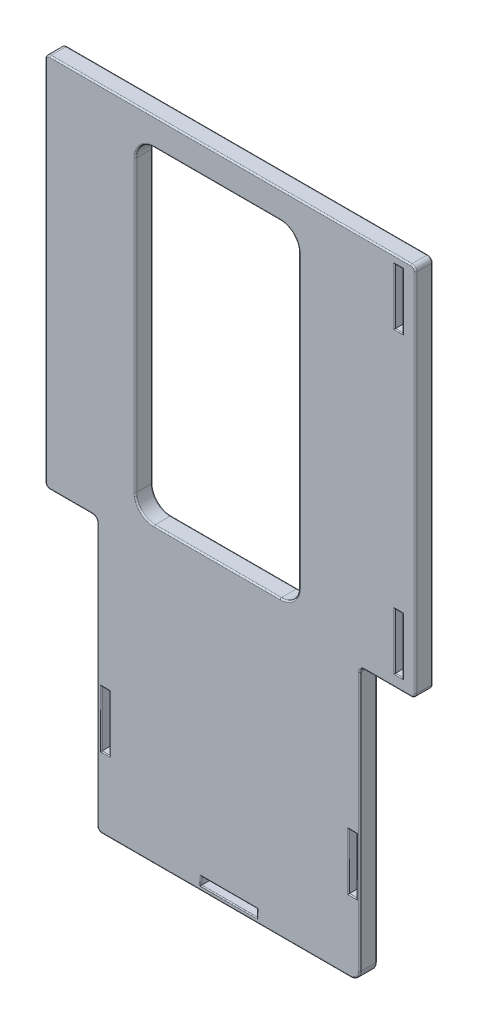
SolidWorks part; units mm, degrees
ref_plane "Front Plane" through (0, 0, 0) normal (0, 0, 1) x (1, 0, 0)
ref_plane "Top Plane" through (0, 0, 0) normal (0, 1, 0) x (1, 0, 0)
ref_plane "Right Plane" through (0, 0, 0) normal (1, 0, 0) x (0, 0, -1)
sketch "Sketch1" plane through (0, 0, 0) normal (0, 0, 1) x (1, 0, 0)
  line L0 (25.4709, 239.3333) -> (35.393, 239.3333)
  line L1 (-19.5605, 313.6323) -> (7.4395, 313.6323)
  line L2 (-23.5605, 309.6323) -> (-23.5605, 247.6323)
  line L3 (-19.5605, 243.6323) -> (7.4395, 243.6323)
  line L4 (11.4395, 309.6323) -> (11.4395, 247.6323)
  line L5 (36.393, 240.3333) -> (36.393, 318.4891)
  line L6 (35.393, 319.4891) -> (-41.857, 319.4891)
  line L7 (-42.857, 318.4891) -> (-42.857, 240.0833)
  line L9 (-41.857, 239.0833) -> (-32.7586, 239.0833)
  line L10 (-31.7586, 238.0833) -> (-31.7586, 181.8891)
  line L16 (-33.0086, 238.8333) -> (-42.107, 238.8333) construction
  line L17 (-32.0086, 209.8891) -> (-32.0086, 237.8333) construction
  line L20 (-32.0086, 181.3891) -> (-32.0086, 209.8891) construction
  line L21 (23.9709, 180.3891) -> (-31.0086, 180.3891) construction
  line L22 (24.9709, 209.8891) -> (24.9709, 181.3891) construction
  line L25 (24.9709, 237.8333) -> (24.9709, 209.8891) construction
  line L44 (34.893, 238.8333) -> (25.9709, 238.8333) construction
  line L61 (36.893, 318.8412) -> (36.893, 240.8333) construction
  line L73 (24.4709, 238.3333) -> (24.4709, 182.8891)
  line L74 (22.4709, 180.8891) -> (-30.7586, 180.8891)
  line L96 (24.9709, 182.3891) -> (24.9709, 217.4411) construction
  line L97 (-22.9709, 180.3891) -> (22.9709, 180.3891) construction
  line L100 (-41.9592, 319.9891) -> (35.7452, 319.9891) construction
  line L101 (-43.107, 239.8333) -> (-43.107, 318.8412) construction
  arc A0 (-23.5605, 247.6323) -> (-19.5605, 243.6323) centre (-19.5605, 247.6323) ccw
  arc A1 (-19.5605, 313.6323) -> (-23.5605, 309.6323) centre (-19.5605, 309.6323) ccw
  arc A5 (7.4395, 313.6323) -> (11.4395, 309.6323) centre (7.4395, 309.6323) cw
  arc A25 (7.4395, 243.6323) -> (11.4395, 247.6323) centre (7.4395, 247.6323) ccw
  arc A29 (-42.857, 240.0833) -> (-41.857, 239.0833) centre (-41.857, 240.0833) ccw
  arc A65 (-32.7586, 239.0833) -> (-31.7586, 238.0833) centre (-32.7586, 238.0833) cw
  arc A66 (-31.7586, 181.8891) -> (-30.7586, 180.8891) centre (-30.7586, 181.8891) ccw
  arc A67 (25.4709, 239.3333) -> (24.4709, 238.3333) centre (25.4709, 238.3333) ccw
  arc A68 (35.393, 239.3333) -> (36.393, 240.3333) centre (35.393, 240.3333) ccw
  arc A69 (36.393, 318.4891) -> (35.393, 319.4891) centre (35.393, 318.4891) ccw
  arc A70 (-41.857, 319.4891) -> (-42.857, 318.4891) centre (-41.857, 318.4891) ccw
  arc A72 (-43.107, 239.8333) -> (-42.107, 238.8333) centre (-42.107, 239.8333) ccw construction
  arc A73 (-32.0086, 237.8333) -> (-33.0086, 238.8333) centre (-33.0086, 237.8333) ccw construction
  arc A74 (-32.0086, 181.3891) -> (-31.0086, 180.3891) centre (-31.0086, 181.3891) ccw construction
  arc A75 (23.9709, 180.3891) -> (24.9709, 181.3891) centre (23.9709, 181.3891) ccw construction
  arc A76 (25.9709, 238.8333) -> (24.9709, 237.8333) centre (25.9709, 237.8333) ccw construction
  arc A77 (34.893, 238.8333) -> (36.893, 240.8333) centre (34.893, 240.8333) ccw construction
  arc A78 (36.893, 318.8412) -> (35.7452, 319.9891) centre (35.7452, 318.8412) ccw construction
  arc A79 (-41.9592, 319.9891) -> (-43.107, 318.8412) centre (-41.9592, 318.8412) ccw construction
  arc A95 (24.4709, 182.8891) -> (22.4709, 180.8891) centre (22.4709, 182.8891) cw
  dimension "D9" = 2
  dimension "D10" = 0.5
  dimension "D11" = 4
  dimension "D14" = 1
  dimension "D2" = 0.5
  dimension "D3" = 0.5
  dimension "D4" = 0.5
  dimension "D5" = 0.5
  dimension "D6" = 0.5
  dimension "D7" = 0.5
  dimension "D8" = 0.5
  dimension "D12" = 35
  dimension "D13" = 70
extrude "Boss-Extrude1" add sketch "Sketch1" along normal blind 3.7
sketch "Sketch2" plane through (0, 0, 0) normal (0, 0, -1) x (-1, 0, 0)
  line L64 (30.8291, 208.1418) -> (30.8291, 196.1418)
  line L65 (30.8291, 196.1418) -> (29.1291, 196.1418)
  line L66 (29.1291, 196.1418) -> (29.1291, 208.1418)
  line L67 (29.1291, 208.1418) -> (30.8291, 208.1418)
  line L68 (9.5291, 183.6091) -> (9.5291, 181.9091)
  line L69 (9.5291, 181.9091) -> (-2.4709, 181.9091)
  line L70 (-2.4709, 181.9091) -> (-2.4709, 183.6091)
  line L71 (-2.4709, 183.6091) -> (9.5291, 183.6091)
  line L72 (-23.7709, 208.1418) -> (-22.0709, 208.1418)
  line L73 (-22.0709, 208.1418) -> (-22.0709, 196.1418)
  line L74 (-22.0709, 196.1418) -> (-23.7709, 196.1418)
  line L75 (-23.7709, 196.1418) -> (-23.7709, 208.1418)
  line L76 (-33.6316, 253.8891) -> (-31.9316, 253.8891)
  line L77 (-31.9316, 253.8891) -> (-31.9316, 241.8891)
  line L78 (-31.9316, 241.8891) -> (-33.6316, 241.8891)
  line L79 (-33.6316, 241.8891) -> (-33.6316, 253.8891)
  line L80 (-33.6316, 305.7891) -> (-33.6316, 317.7891)
  line L81 (-33.6316, 317.7891) -> (-31.9316, 317.7891)
  line L82 (-31.9316, 317.7891) -> (-31.9316, 305.7891)
  line L83 (-31.9316, 305.7891) -> (-33.6316, 305.7891)
  line L84 (-36.393, 240.3333) -> (-36.393, 318.4891) construction
  line L85 (-35.393, 319.4891) -> (41.857, 319.4891) construction
  line L86 (-25.4709, 239.3333) -> (-35.393, 239.3333) construction
  line L87 (-24.4709, 182.8891) -> (-24.4709, 238.3333) construction
  line L88 (30.7586, 180.8891) -> (-22.4709, 180.8891) construction
  line L89 (31.7586, 238.0833) -> (31.7586, 181.8891) construction
  dimension "D3" = 12
  dimension "D1" = 1.7
  dimension "D2" = 12
  dimension "D4" = 2.7614
  dimension "D5" = 1.7
  dimension "D6" = 1.7
  dimension "D7" = 12
  dimension "D8" = 2.7614
  dimension "D9" = 2.5557
  dimension "D10" = 1.7
  dimension "D11" = 12
  dimension "D12" = 0.7
  dimension "D13" = 1.7
  dimension "D14" = 1.02
  dimension "D15" = 22.2295
  dimension "D16" = 1.7
  dimension "D17" = 12
  dimension "D18" = 0.9295
  dimension "D19" = 15.2527
  dimension "D20" = 15.2527
extrude "Cut-Extrude1" cut sketch "Sketch2" against normal blind 4
fillet "Fillet1" radius 0.3 48 edges at (-22.389, 244.8039, 3.7) (-23.5605, 278.6323, 3.7) (-22.389, 312.4607, 3.7) (-6.0605, 313.6323, 3.7) (10.2679, 312.4607, 3.7) (11.4395, 278.6323, 3.7) (10.2679, 244.8039, 3.7) (-22.389, 244.8039, 0) (-23.5605, 278.6323, 0) (-22.389, 312.4607, 0) (-6.0605, 313.6323, 0) (10.2679, 312.4607, 0) (11.4395, 278.6323, 0) (10.2679, 244.8039, 0) (24.4709, 210.6112, 0) (24.7638, 239.0404, 0) (30.432, 239.3333, 0) (36.1001, 239.6262, 0) (36.1001, 239.6262, 3.7) (30.432, 239.3333, 3.7) (24.7638, 239.0404, 3.7) (24.4709, 210.6112, 3.7) (23.8851, 181.4748, 3.7) (-4.1438, 180.8891, 3.7) (-31.4657, 181.182, 3.7) (-31.7586, 209.9862, 3.7) (-32.0515, 238.7904, 3.7) (-37.3078, 239.0833, 3.7) (-42.5641, 239.3762, 3.7) (-42.857, 279.2862, 3.7) (-42.5641, 319.1962, 3.7) (-3.232, 319.4891, 3.7) (36.1001, 319.1962, 3.7) (-31.7586, 209.9862, 0) (-32.0515, 238.7904, 0) (-37.3078, 239.0833, 0) (-42.5641, 239.3762, 0) (-42.857, 279.2862, 0) (-42.5641, 319.1962, 0) (-3.232, 319.4891, 0) (36.1001, 319.1962, 0) (-6.0605, 243.6323, 3.7) (-6.0605, 243.6323, 0) (36.393, 279.4112, 0) (36.393, 279.4112, 3.7) (23.8851, 181.4748, 0) (-4.1438, 180.8891, 0) (-31.4657, 181.182, 0)
fillet "Fillet2" radius 0.2 40 edges at (31.9316, 311.7891, 0) (32.7816, 317.7891, 0) (33.6316, 311.7891, 0) (32.7816, 305.7891, 0) (32.7816, 241.8891, 0) (31.9316, 247.8891, 0) (32.7816, 253.8891, 0) (33.6316, 247.8891, 0) (22.9209, 196.1418, 0) (22.0709, 202.1418, 0) (22.9209, 208.1418, 0) (23.7709, 202.1418, 0) (2.4709, 182.7591, 0) (-3.5291, 181.9091, 0) (-9.5291, 182.7591, 0) (-3.5291, 183.6091, 0) (-29.1291, 202.1418, 0) (-29.9791, 196.1418, 0) (-30.8291, 202.1418, 0) (-29.9791, 208.1418, 0) (32.7816, 317.7891, 3.7) (31.9316, 311.7891, 3.7) (32.7816, 305.7891, 3.7) (33.6316, 311.7891, 3.7) (31.9316, 247.8891, 3.7) (32.7816, 241.8891, 3.7) (33.6316, 247.8891, 3.7) (32.7816, 253.8891, 3.7) (22.0709, 202.1418, 3.7) (22.9209, 196.1418, 3.7) (23.7709, 202.1418, 3.7) (22.9209, 208.1418, 3.7) (-3.5291, 181.9091, 3.7) (2.4709, 182.7591, 3.7) (-3.5291, 183.6091, 3.7) (-9.5291, 182.7591, 3.7) (-29.9791, 196.1418, 3.7) (-29.1291, 202.1418, 3.7) (-29.9791, 208.1418, 3.7) (-30.8291, 202.1418, 3.7)
